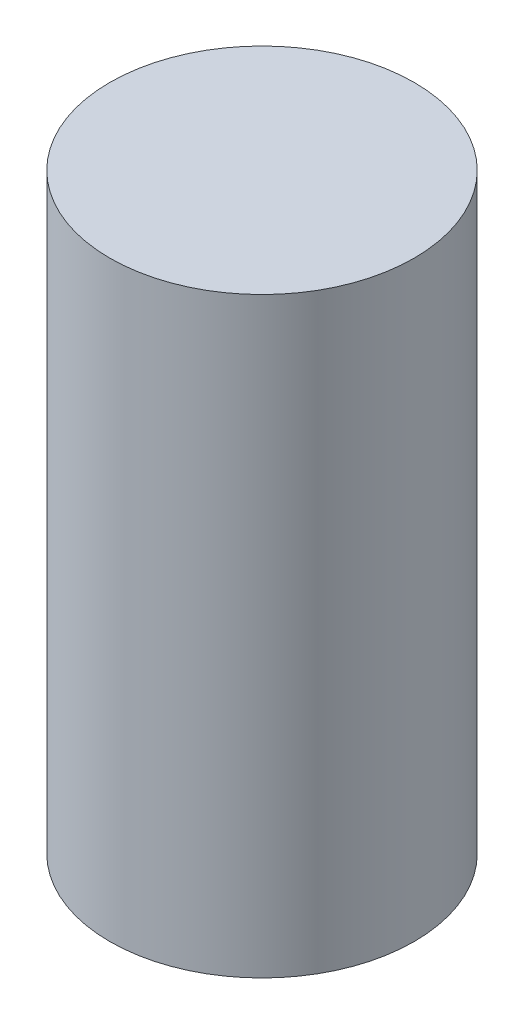
SolidWorks part; units mm, degrees
ref_plane "前视基准面" through (0, 0, 0) normal (0, 0, 1) x (1, 0, 0)
ref_plane "上视基准面" through (0, 0, 0) normal (0, 1, 0) x (1, 0, 0)
ref_plane "右视基准面" through (0, 0, 0) normal (1, 0, 0) x (0, 0, -1)
other "Configuration Table"
sketch "草图1" plane through (0, 0, 0) normal (0, 1, 0) x (1, 0, 0)
  circle A0 centre (0, 0) radius 9
  dimension "D1" = 18
extrude "凸台-拉伸1" add sketch "草图1" along normal blind 35
